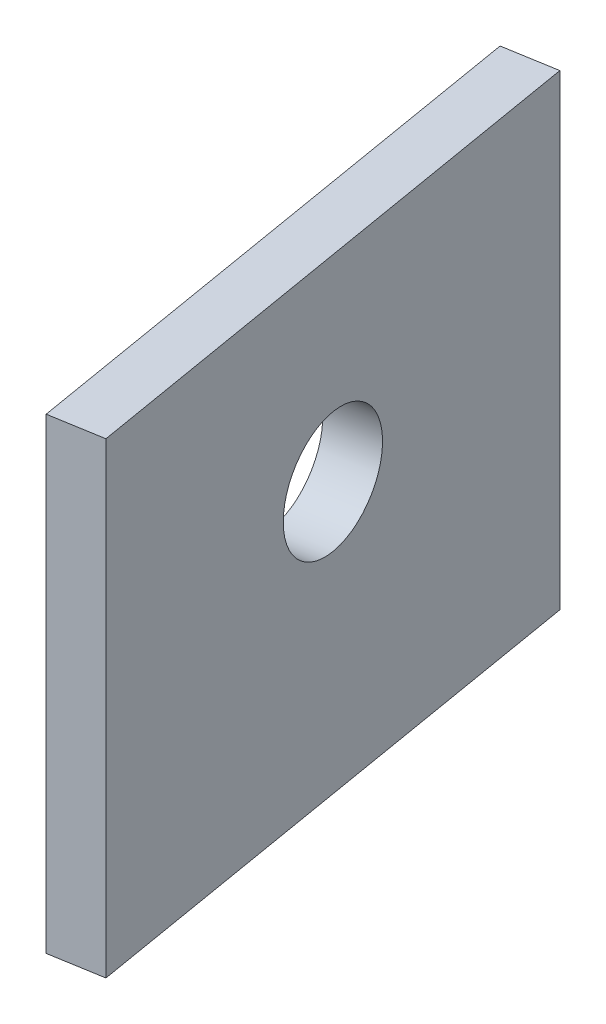
SolidWorks part; units mm, degrees
ref_plane "Alzado" through (0, 0, 0) normal (0, 0, 1) x (1, 0, 0)
ref_plane "Planta" through (0, 0, 0) normal (0, 1, 0) x (1, 0, 0)
ref_plane "Vista lateral" through (0, 0, 0) normal (1, 0, 0) x (0, 0, -1)
sketch "Croquis1" plane through (30.782, 0, -5.1822) normal (0.9861, 0, -0.166) x (-0.166, 0, -0.9861)
  line L0 (-182.2485, 22.7) -> (-182.2485, 11.3355) construction
  line L1 (-190.2485, 22.7) -> (-174.2485, 22.7)
  line L2 (-190.2485, 22.7) -> (-190.2485, 9.2)
  line L3 (-190.2485, 9.2) -> (-174.2485, 9.2)
  line L4 (-174.2485, 22.7) -> (-174.2485, 9.2)
  line L5 (-176.7485, 22.3355) -> (-187.7485, 22.3355) construction
  line L6 (-176.7485, 22.3355) -> (-176.7485, 11.3355) construction
  line L7 (-176.7485, 11.3355) -> (-187.7485, 11.3355) construction
  line L8 (-187.7485, 22.3355) -> (-187.7485, 11.3355) construction
  line L9 (-187.7485, 16.8355) -> (-176.7485, 16.8355) construction
  circle A0 centre (-182.2485, 17.0178) radius 1.75
  dimension "D3" = 3.5
  dimension "D1" = 13.5
  dimension "D2" = 16
extrude "Saliente-Extruir1" add sketch "Croquis1" along normal blind 1.5
